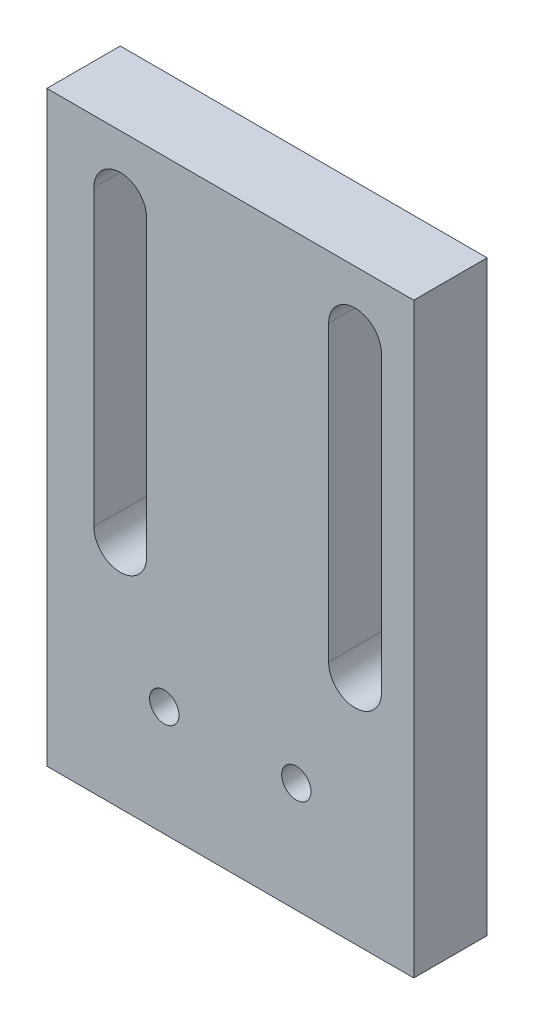
SolidWorks part; units mm, degrees
ref_plane "Front Plane" through (0, 0, 0) normal (0, 0, 1) x (1, 0, 0)
ref_plane "Top Plane" through (0, 0, 0) normal (0, 1, 0) x (1, 0, 0)
ref_plane "Right Plane" through (0, 0, 0) normal (1, 0, 0) x (0, 0, -1)
sketch "Sketch1" plane through (0, 0, 0) normal (0, 0, 1) x (1, 0, 0)
  line L0 (-8, 23.9935) -> (-8, 3.9935) construction
  line L1 (-13, 28.2528) -> (12, 28.2528)
  line L2 (-13, 28.2528) -> (-13, -11.7472)
  line L3 (-13, -11.7472) -> (12, -11.7472)
  line L4 (12, 28.2528) -> (12, -11.7472)
  line L5 (-6.2, 23.9935) -> (-6.2, 3.9935)
  line L6 (-9.8, 23.9935) -> (-9.8, 3.9935)
  line L7 (0, 29.5292) -> (0, 4.8864) construction
  line L8 (8, 23.9935) -> (8, 3.9935) construction
  line L9 (6.2, 23.9935) -> (6.2, 3.9935)
  line L10 (9.8, 23.9935) -> (9.8, 3.9935)
  circle A0 centre (-5, -4.2472) radius 1
  circle A1 centre (4, -4.2472) radius 1
  arc A2 (-6.2, 23.9935) -> (-9.8, 23.9935) centre (-8, 23.9935) ccw
  arc A3 (-9.8, 3.9935) -> (-6.2, 3.9935) centre (-8, 3.9935) ccw
  arc A4 (6.2, 23.9935) -> (9.8, 23.9935) centre (8, 23.9935) cw
  arc A5 (9.8, 3.9935) -> (6.2, 3.9935) centre (8, 3.9935) cw
  point P10 (-8, 13.9935)
  point P20 (8, 13.9935)
  dimension "D3" = 9
  dimension "D4" = 8
  dimension "D5" = 2
  dimension "D6" = 2
  dimension "D8" = 20
  dimension "D9" = 7.5
  dimension "D10" = 1.8
  dimension "D1" = 25
  dimension "D2" = 40
  dimension "D7" = 5
  dimension "D11" = 8
extrude "Boss-Extrude1" add sketch "Sketch1" along normal blind 5
sketch "Sketch2" plane through (0, 0, 0) normal (0, 0, -1) x (-1, 0, 0)
  line L1 (-7.1, -1.1472) -> (-0.9, -1.1472)
  line L2 (-7.1, -1.1472) -> (-7.1, -7.3472)
  line L3 (-7.1, -7.3472) -> (-0.9, -7.3472)
  line L4 (-0.9, -1.1472) -> (-0.9, -7.3472)
  line L5 (-7.1, -1.1472) -> (-0.9, -7.3472) construction
  line L6 (-7.1, -7.3472) -> (-0.9, -1.1472) construction
  line L7 (1.9, -1.1472) -> (8.1, -1.1472)
  line L8 (1.9, -1.1472) -> (1.9, -7.3472)
  line L9 (1.9, -7.3472) -> (8.1, -7.3472)
  line L10 (8.1, -1.1472) -> (8.1, -7.3472)
  line L11 (1.9, -1.1472) -> (8.1, -7.3472) construction
  line L12 (1.9, -7.3472) -> (8.1, -1.1472) construction
  point P0 (-4, -4.2472)
  point P6 (5, -4.2472)
  dimension "D1" = 6.2
  dimension "D2" = 6.2
  dimension "D3" = 6.2
  dimension "D4" = 6.2
extrude "Cut-Extrude1" cut sketch "Sketch2" against normal blind 2.5
